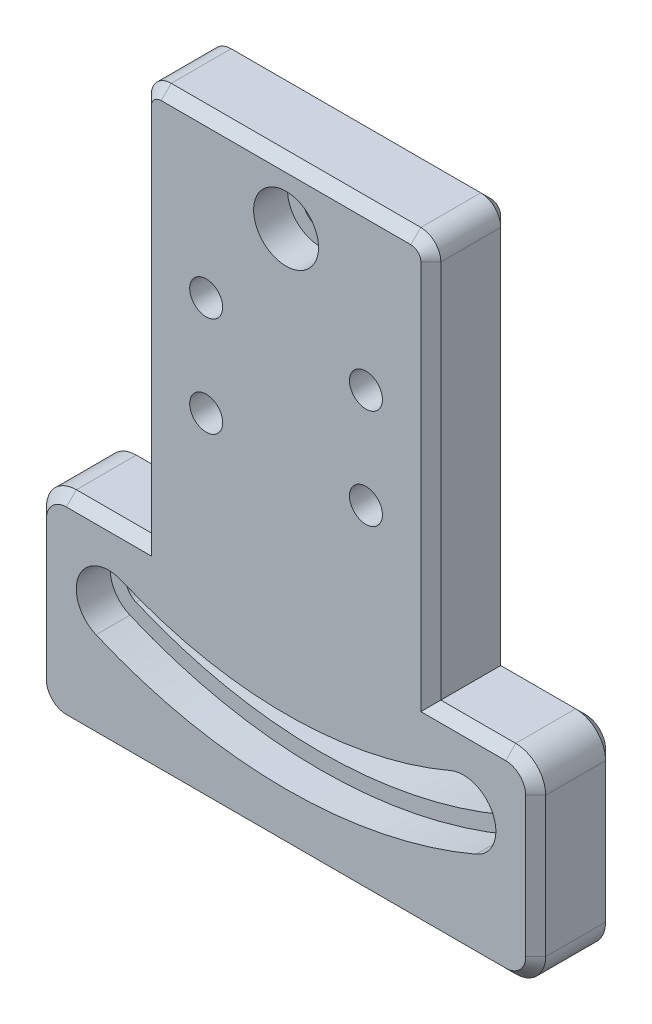
SolidWorks part; units mm, degrees
material "Alumina"
ref_plane "Front Plane" through (0, 0, 0) normal (0, 0, 1) x (1, 0, 0)
ref_plane "Top Plane" through (0, 0, 0) normal (0, 1, 0) x (1, 0, 0)
ref_plane "Right Plane" through (0, 0, 0) normal (1, 0, 0) x (0, 0, -1)
sketch "Sketch1" plane through (0, 0, 0) normal (0, 0, 1) x (1, 0, 0)
  line L1 (-25, 36.5) -> (25, 36.5)
  line L2 (-25, 36.5) -> (-25, -36.5)
  line L3 (-25, -36.5) -> (25, -36.5)
  line L4 (25, 36.5) -> (25, -36.5)
  line L5 (-25, 36.5) -> (25, -36.5) construction
  line L6 (-25, -36.5) -> (25, 36.5) construction
  point P0 (0, 0)
  dimension "D1" = 50
  dimension "D2" = 73
extrude "Boss-Extrude1" add sketch "Sketch1" along normal blind 8
hole_wizard "CBORE for M3 Hex Socket Head Cap Screw1" positions "Sketch2" profile "Sketch3" counterbore size "M3" standard "DIN" end condition through all
sketch "Sketch2" plane through (0, 0, 8) normal (0, 0, 1) x (1, 0, 0)
  line L1 (-25, -36.5) -> (25, -36.5) construction
  point P0 (0, 17.64)
  dimension "D1" = 54.14
sketch "Sketch3" plane through (0, 17.64, 8) normal (1, 0, 0) x (0, -1, 0)
  line L0 (0, 0) -> (0, 8)
  line L1 (0, 8) -> (1.7, 8)
  line L3 (1.7, 8) -> (1.7, 3.4)
  line L4 (1.7, 3.4) -> (3.25, 3.4)
  line L5 (3.25, 3.4) -> (3.25, 0)
  line L7 (3.25, 0) -> (0, 0)
  line L11 (0, -6.35) -> (0, 107.95) construction
  dimension "Thru Hole Dia." = 3.4
  dimension "Thru Hole Depth" = 8
  dimension "C'Bore Dia." = 6.5
  dimension "C'Bore Depth" = 3.4
sketch "Sketch5" plane through (0, 0, 8) normal (0, 0, 1) x (1, 0, 0)
  line L2 (0, 17.64) -> (0, -65.3635) construction
  arc A4 (-17.7618, -24.1105) -> (17.7618, -24.1105) centre (0, 17.64) ccw construction
  arc A9 (-19.0341, -27.1011) -> (19.0341, -27.1011) centre (0, 17.64) ccw
  arc A10 (-16.4896, -21.1199) -> (16.4896, -21.1199) centre (0, 17.64) ccw
  arc A11 (-16.4896, -21.1199) -> (-19.0341, -27.1011) centre (-17.7618, -24.1105) ccw
  arc A12 (19.0341, -27.1011) -> (16.4896, -21.1199) centre (17.7618, -24.1105) ccw
  point P2 (0, -27.7317)
extrude "Cut-Extrude1" cut sketch "Sketch5" against normal blind 3.4
sketch "Sketch6" plane through (0, 0, 4.6) normal (0, 0, 1) x (1, 0, 0)
  arc A3 (-17.7618, -24.1105) -> (17.7618, -24.1105) centre (0, 17.64) ccw construction
  arc A4 (-18.4274, -25.6748) -> (18.4274, -25.6748) centre (0, 17.64) ccw
  arc A5 (-17.0963, -22.5462) -> (17.0963, -22.5462) centre (0, 17.64) ccw
  arc A6 (-17.0963, -22.5462) -> (-18.4274, -25.6748) centre (-17.7618, -24.1105) ccw
  arc A7 (18.4274, -25.6748) -> (17.0963, -22.5462) centre (17.7618, -24.1105) ccw
  point P9 (0, -27.7317)
extrude "Cut-Extrude2" cut sketch "Sketch6" against normal blind 16.4
sketch "Sketch9" plane through (0, 0, 8) normal (0, 0, 1) x (1, 0, 0)
  line L0 (25, -36.5) -> (25, 36.5) construction
  line L3 (-25, 23.5) -> (25, 23.5)
  line L6 (-25, 23.5) -> (31.4082, 23.5)
  line L7 (-25, 23.5) -> (-25, 42.8001)
  line L8 (-25, 42.8001) -> (31.4082, 42.8001)
  line L9 (31.4082, 23.5) -> (31.4082, 42.8001)
  line M14 (25, -36.5) -> (25, 36.5)
  line M15 (25, 36.5) -> (-25, 36.5)
  line M16 (-25, 36.5) -> (-25, -36.5)
extrude "Cut-Extrude3" cut sketch "Sketch9" against normal blind 10 contours L3 M16 M14 M15
sketch "Sketch10" plane through (0, 0, 8) normal (0, 0, 1) x (1, 0, 0)
  line L0 (0, 27.4238) -> (0, 7.1266) construction
  line L1 (-25, 23.5) -> (25, 23.5) construction
  line L3 (-14.5, 23.5) -> (-14.5, -16.5)
  line L5 (14.5, 23.5) -> (14.5, -16.5)
  line L6 (-14.5, 23.5) -> (14.5, 23.5)
  line L7 (-14.5, -16.5) -> (-25, -16.5)
  line L8 (-25, 23.5) -> (-25, -36.5) construction
  line L9 (14.5, -16.5) -> (25, -16.5)
  line L10 (25, -36.5) -> (25, 23.5) construction
  line L14 (-32.8672, -16.5) -> (-25, -16.5)
  line L15 (-32.8672, -16.5) -> (-35.3493, 40.2075)
  line L16 (-35.3493, 40.2075) -> (-6.1065, 43.004)
  line L17 (-6.1065, 43.004) -> (18.0408, 43.004)
  line L18 (18.0408, 43.004) -> (35.5557, 29.2667)
  line L19 (35.5557, 29.2667) -> (37.9664, 22.6931)
  line L20 (37.9664, 22.6931) -> (41.9414, 11.8538)
  line L21 (41.9414, 11.8538) -> (39.9539, 3.91)
  line L22 (39.9539, 3.91) -> (32.2124, -8.8255)
  line L23 (32.2124, -8.8255) -> (28.6014, -14.766)
  line L24 (28.6014, -14.766) -> (25, -16.5)
  point P3 (0, 23.5)
  dimension "D3" = 40
extrude "Cut-Extrude6" cut sketch "Sketch10" against normal blind 49
fillet "Fillet1" radius 3 4 edges at (25, -16.5, 4) (-25, -16.5, 4) (25, -36.5, 4) (-25, -36.5, 4)
fillet "Fillet2" radius 2 2 edges at (-14.5, 23.5, 4) (14.5, 23.5, 4)
hole_wizard "M4 Tapped Hole1" positions "Sketch11" profile "Sketch12" tap size "M4" standard "DIN"
sketch "Sketch11" plane through (0, 0, 8) normal (0, 0, 1) x (1, 0, 0)
  circle A0 centre (0, 17.64) radius 3.25 construction
  point P0 (-8, -2.36)
  point P2 (8, -2.36)
  point P8 (-8, 7.64)
  point P10 (8, 7.64)
  dimension "D1" = 8
  dimension "D2" = 8
  dimension "D3" = 20
  dimension "D4" = 20
  dimension "D5" = 10
  dimension "D6" = 10
sketch "Sketch12" plane through (-8, -2.36, 8) normal (1, 0, 0) x (0, -1, 0)
  line L0 (0, 0) -> (0, 6.9914)
  line L1 (0, 6.9914) -> (1.65, 6)
  line L2 (1.65, 6) -> (1.65, 0)
  line L5 (1.65, 0) -> (0, 0)
  line L10 (0, 6.9914) -> (-1.65, 6) construction
  line L11 (0, -6.35) -> (0, 107.95) construction
  dimension "Tap Drill Dia." = 3.3
  dimension "Tap Drill Depth" = 6
  dimension "Drill Angle" = 118
cosmetic thread "Hole Thread4" parameters "D1"=5, "D2"=4
cosmetic thread "Hole Thread5" parameters "D1"=5, "D2"=4
cosmetic thread "Hole Thread6" parameters "D1"=5, "D2"=4
cosmetic thread "Hole Thread7" parameters "D1"=5, "D2"=4
sketch "Sketch14" plane through (0, 0, 0) normal (0, 0, -1) x (-1, 0, 0)
  line L0 (-12, -36.5) -> (12, -36.5) construction
  line L1 (22, -36.5) -> (-22, -36.5) construction
  line L2 (-12, -33.5) -> (12, -33.5)
  line L4 (-25, -33.5) -> (-25, -19.5) construction
  line L5 (25, -19.5) -> (25, -33.5) construction
  line L6 (-15, -36.5) -> (15, -36.5)
  arc A0 (-12, -33.5) -> (-15, -36.5) centre (-12, -36.5) ccw
  arc A1 (15, -36.5) -> (12, -33.5) centre (12, -36.5) ccw
  point P4 (0, -36.5)
  dimension "D1" = 13
  dimension "D2" = 13
extrude "Cut-Extrude9" cut sketch "Sketch14" against normal blind 1
chamfer "Chamfer2" distance 1 angle 45 24 edges at (-18.25, -16.5, 8) (18.25, -16.5, 8) (-24.1213, -17.3787, 8) (24.1213, -17.3787, 8) (-25, -26.5, 8) (25, -26.5, 8) (-24.1213, -35.6213, 8) (24.1213, -35.6213, 8) (0, -36.5, 8) (-14.5, 2.5, 0) (-13.9142, 22.9142, 0) (0, 23.5, 0) (13.9142, 22.9142, 0) (14.5, 2.5, 0) (18.25, -16.5, 0) (24.1213, -17.3787, 0) (25, -26.5, 0) (24.1213, -35.6213, 0) (18.5, -36.5, 0) (-18.25, -16.5, 0) (-24.1213, -17.3787, 0) (-25, -26.5, 0) (-24.1213, -35.6213, 0) (-18.5, -36.5, 0)
chamfer "Chamfer3" distance 1 angle 45 5 edges at (14.5, 2, 8) (13.9142, 22.9142, 8) (0, 23.5, 8) (-13.9142, 22.9142, 8) (-14.5, 2, 8)
